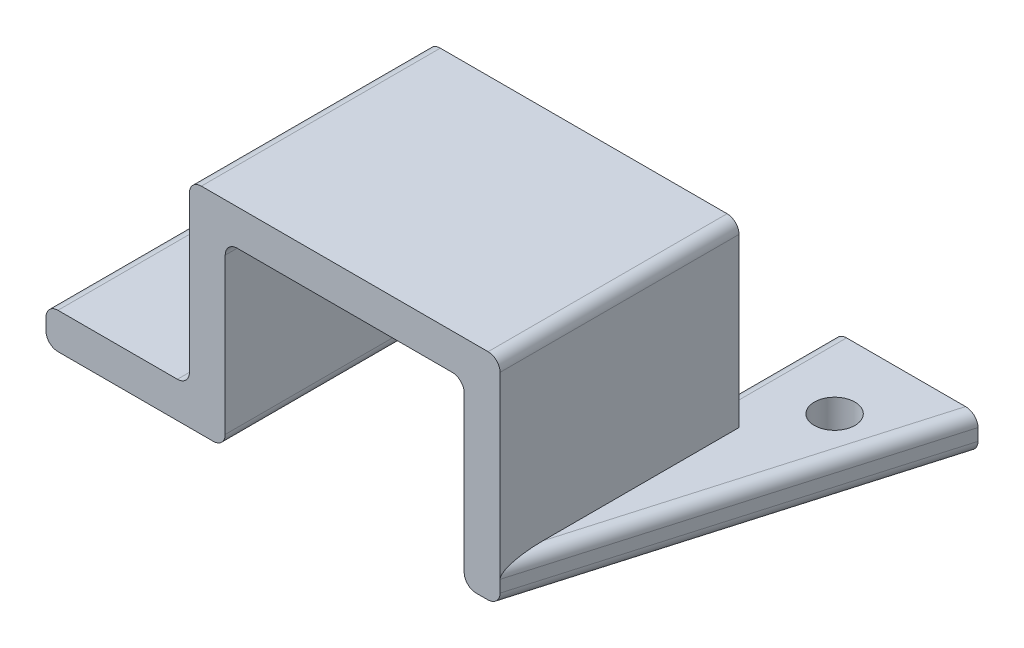
SolidWorks part; units mm, degrees
ref_plane "Front Plane" through (0, 0, 0) normal (0, 0, 1) x (1, 0, 0)
ref_plane "Top Plane" through (0, 0, 0) normal (0, 1, 0) x (1, 0, 0)
ref_plane "Right Plane" through (0, 0, 0) normal (1, 0, 0) x (0, 0, -1)
sketch "Sketch3" plane through (0, 0, 0) normal (0, 0, 1) x (1, 0, 0)
  line L12 (3, 0) -> (3, 15)
  line L13 (3, 15) -> (23, 15)
  line L14 (23, 15) -> (23, 0)
  line L15 (23, 0) -> (26, 0)
  line L16 (26, 0) -> (26, 18)
  line L17 (26, 18) -> (0, 18)
  line L19 (0, 18) -> (0, 0)
  line L20 (0, 0) -> (3, 0)
  point P7 (-15.688, 24.4837)
  point P9 (0, 0)
  dimension "D1" = 3
  dimension "D2" = 3
  dimension "D4" = 20
  dimension "D3" = 15
extrude "Boss-Extrude1" add sketch "Sketch3" along normal blind 20
sketch "Sketch7" plane through (0, 0, 0) normal (0, 1, 0) x (1, 0, 0)
  line L0 (26, -20) -> (35, 11)
  line L1 (35, 11) -> (23, 11)
  line L2 (23, 11) -> (23, 0)
  line L3 (26, 0) -> (0, 0) construction
  line L4 (13, 0) -> (13, 9.0562) construction
  line L8 (23, 0) -> (26, 0) construction
  line L9 (26, -20) -> (26, 0)
  line L10 (26, 0) -> (23, 0)
  line L13 (-12, 11) -> (131, 11) construction
  line L14 (-12, -20) -> (-12, 11) construction
  line L15 (0, -20) -> (-12, -20)
  line L16 (0, -20) -> (0, 0)
  line L17 (0, 0) -> (-12, 0)
  line L18 (-12, -20) -> (-12, 0)
  point P9 (-6, -10)
  point P15 (29, 5)
  point P33 (-12, -10)
  dimension "D1" = 5
  dimension "D2" = 6
  dimension "D3" = 12
  dimension "D4" = 6
extrude "Boss-Extrude2" add sketch "Sketch7" along normal blind 3
sketch "Sketch8" plane through (0, 3, 0) normal (0, 1, 0) x (1, 0, 0)
  point P2 (29, 5)
  point P5 (-6, -10)
hole_wizard "M3 Clearance Hole2" positions "Sketch8" profile "Sketch9" hole size "M3" standard "ANSI Metric" end condition through all
sketch "Sketch9" plane through (29, 3, -5) normal (1, 0, 0) x (0, 0, 1)
  line L0 (0, 0) -> (0, 3)
  line L1 (0, 3) -> (1.7, 3)
  line L2 (1.7, 3) -> (1.7, 0)
  line L5 (1.7, 0) -> (0, 0)
  line L11 (0, -6.35) -> (0, 107.95) construction
  dimension "Thru Hole Dia." = 3.4
  dimension "Thru Hole Depth" = 3
fillet "Fillet1" radius 1 12 edges at (3, 0, 10) (-12, 0, 10) (-12, 3, 10) (0, 3, 10) (23, 3, -5.5) (23, 0, 4.5) (0, 18, 10) (30.5, 3, 4.5) (30.5, 0, 4.5) (26, 18, 10) (3, 15, 10) (23, 15, 10)
sketch "Sketch4" plane through (0, 0, 0) normal (0, 1, 0) x (1, 0, 0)
  line L0 (-25, -20) -> (-25, 0) construction
  line L1 (-15, 0) -> (-25, 0) construction
  line L2 (0, 0) -> (0, -3.6172) construction
  line L3 (15, 0) -> (-15, 0) construction
  point P0 (-20, -10)
  point P4 (-25, -10)
  point P7 (-20, 0)
  point P8 (20, -10)
hole_wizard "M3 Clearance Hole1" positions "Sketch4" profile "Sketch5" hole size "M3" standard "ANSI Metric"
sketch "Sketch5" plane through (-20, 0, 10) normal (1, 0, 0) x (0, 0, -1)
  line L0 (0, 0) -> (0, 20)
  line L1 (0, 20) -> (1.7, 20)
  line L2 (1.7, 20) -> (1.7, 0)
  line L5 (1.7, 0) -> (0, 0)
  line L11 (0, -6.35) -> (0, 107.95) construction
  dimension "Thru Hole Dia." = 3.4
  dimension "Thru Hole Depth" = 20
